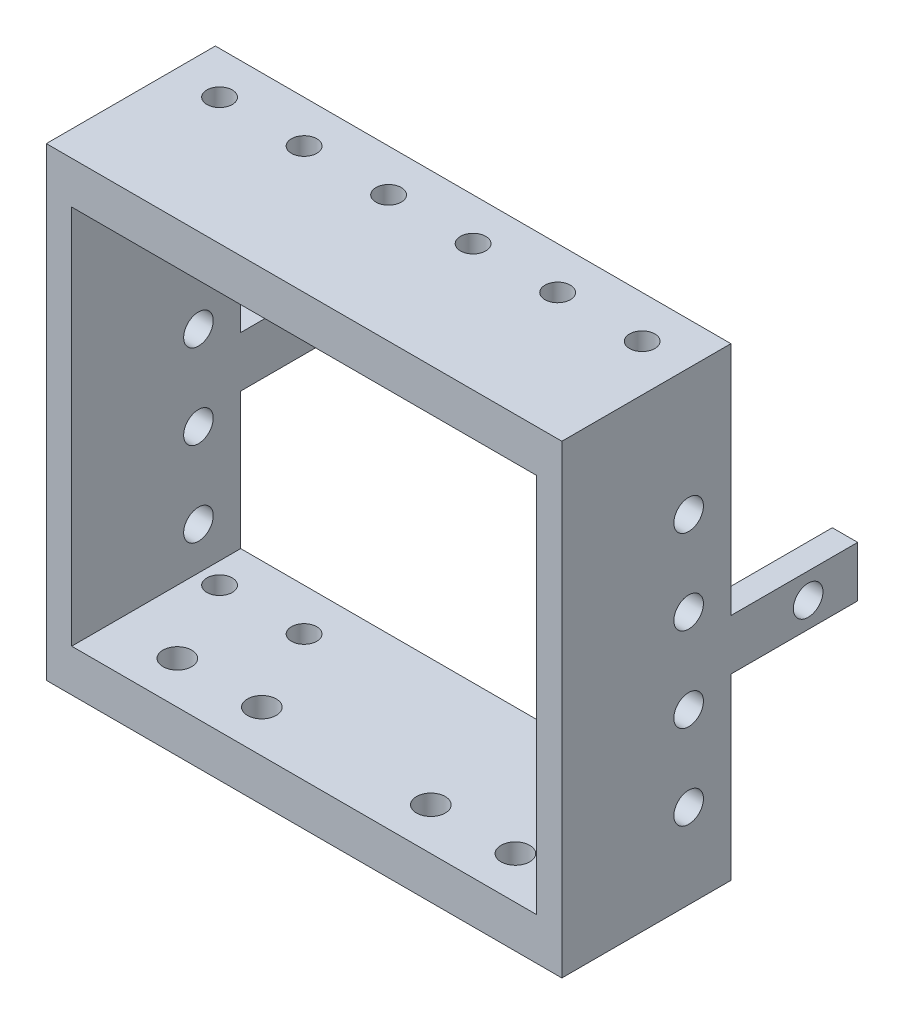
SolidWorks part; units mm, degrees
ref_plane "Front Plane" through (0, 0, 0) normal (0, 0, 1) x (1, 0, 0)
ref_plane "Top Plane" through (0, 0, 0) normal (0, 1, 0) x (1, 0, 0)
ref_plane "Right Plane" through (0, 0, 0) normal (1, 0, 0) x (0, 0, -1)
sketch "Sketch1" plane through (0, 0, 0) normal (0, 1, 0) x (1, 0, 0)
  line L1 (-23.3554, -4.3957) -> (37.6446, -4.3957)
  line L2 (-23.3554, -4.3957) -> (-23.3554, 5.6043)
  line L3 (-23.3554, 5.6043) -> (37.6446, 5.6043)
  line L4 (37.6446, -4.3957) -> (37.6446, 5.6043)
  circle A0 centre (-17.8554, 0.6043) radius 1.5
  circle A1 centre (-7.8554, 0.6043) radius 1.5
  circle A2 centre (22.1446, 0.6043) radius 1.5
  circle A3 centre (32.1446, 0.6043) radius 1.5
  dimension "D5" = 3
  dimension "D1" = 10
  dimension "D2" = 10
  dimension "D3" = 5.5
  dimension "D4" = 5.5
  dimension "D6" = 10
  dimension "D7" = 30
  dimension "D8" = 5
extrude "Boss-Extrude1" add sketch "Sketch1" along normal blind 5
sketch "Sketch2" plane through (0, 5, 0) normal (0, 1, 0) x (1, 0, 0)
  line L0 (37.6446, -4.3957) -> (37.6446, 5.6043) construction
  line L1 (-23.3554, -4.3957) -> (37.6446, -4.3957) construction
  line L2 (-23.3554, 5.6043) -> (-23.3554, -4.3957) construction
  line L3 (37.6446, 5.6043) -> (-23.3554, 5.6043) construction
  line L4 (37.6446, -4.3957) -> (37.6446, 5.6043)
  line L5 (-23.3554, -4.3957) -> (-20.3554, -4.3957)
  line L6 (-23.3554, 5.6043) -> (-23.3554, -4.3957)
  line L7 (37.6446, 5.6043) -> (34.6446, 5.6043)
  line L8 (-20.3554, 5.6043) -> (-20.3554, -4.3957)
  line L9 (34.6446, 5.6043) -> (34.6446, -4.3957)
  line L10 (-20.3554, 5.6043) -> (-23.3554, 5.6043)
  line L11 (34.6446, -4.3957) -> (37.6446, -4.3957)
  dimension "D1" = 3
  dimension "D2" = 3
extrude "Boss-Extrude2" add sketch "Sketch2" along normal blind 45
sketch "Sketch3" plane through (-23.3554, 0, 0) normal (-1, 0, 0) x (0, 0, 1)
  line L0 (-5.6043, 5) -> (4.3957, 5) construction
  line L1 (-5.6043, 5) -> (4.3957, 5) construction
  line L2 (-5.6043, 50) -> (-5.6043, 0) construction
  circle A0 centre (-0.6043, 10) radius 1.75
  dimension "D1" = 3.5
  dimension "D2" = 5
  dimension "D3" = 5
extrude "Cut-Extrude1" cut sketch "Sketch3" against normal through all contours A0
sketch "Sketch4" plane through (-23.3554, 0, 0) normal (-1, 0, 0) x (0, 0, 1)
  line L0 (-5.6043, 50) -> (-5.6043, 0) construction
  line L1 (-5.6043, 21.14) -> (-20.6043, 21.14)
  line L2 (-5.6043, 21.14) -> (-5.6043, 27.14)
  line L3 (-5.6043, 27.14) -> (-20.6043, 27.14)
  line L4 (-20.6043, 21.14) -> (-20.6043, 27.14)
  circle A0 centre (-14.7443, 24.14) radius 1.75
  circle A1 centre (-0.6043, 10) radius 1.75 construction
  dimension "D1" = 3.5
  dimension "D3" = 14.14
  dimension "D5" = 3
  dimension "D2" = 14.14
  dimension "D4" = 6
  dimension "D6" = 15
extrude "Boss-Extrude3" add sketch "Sketch4" against normal blind 3 contours L1 L4 L3 L2
ref_plane "Plane1" through (7.1446, 0, 0) normal (-1, 0, 0) x (0, 0, 1)
mirror "Mirror1" about plane through (7.1446, 0, 0) normal (-1, 0, 0) of "Boss-Extrude3"
sketch "Sketch5" plane through (-23.3554, 0, 0) normal (-1, 0, 0) x (0, 0, 1)
  circle A0 centre (-14.7443, 24.14) radius 1.75
  circle A1 centre (-0.6043, 10) radius 1.75 construction
  dimension "D1" = 3.5
  dimension "D2" = 14.14
  dimension "D3" = 14.14
extrude "Cut-Extrude2" cut sketch "Sketch5" against normal through all
sketch "Sketch6" plane through (0, 50, 0) normal (0, 1, 0) x (1, 0, 0)
  line L0 (7.1446, 13.75) -> (7.1446, -13.75) construction
  line L1 (-23.3554, -4.3957) -> (37.6446, -4.3957)
  line L2 (-23.3554, -4.3957) -> (-23.3554, 5.6043)
  line L3 (-23.3554, 5.6043) -> (37.6446, 5.6043)
  line L4 (37.6446, -4.3957) -> (37.6446, 5.6043)
  circle A0 centre (2.1446, 0.6043) radius 1.5
  circle A1 centre (12.1446, 0.6043) radius 1.5
  circle A2 centre (-7.8554, 0.6043) radius 1.5
  circle A3 centre (-17.8554, 0.6043) radius 1.5
  circle A4 centre (22.1446, 0.6043) radius 1.5
  circle A5 centre (32.1446, 0.6043) radius 1.5
  dimension "D1" = 3
  dimension "D2" = 5
  dimension "D3" = 5
  dimension "D4" = 3
  dimension "D5" = 3
extrude "Boss-Extrude4" add sketch "Sketch6" along normal blind 5
sketch "Sketch7" plane through (-23.3554, 0, 0) normal (-1, 0, 0) x (0, 0, 1)
  circle A0 centre (-0.6043, 10) radius 1.75 construction
  circle A1 centre (-0.6043, 10) radius 1.75
  circle A2 centre (-0.6043, 20) radius 1.75
  circle A3 centre (-0.6043, 30) radius 1.75
  circle A4 centre (-0.6043, 40) radius 1.75
  circle A6 centre (-0.6043, 50) radius 1.75 [skipped]
  dimension "D1" = 5
extrude "Cut-Extrude3" cut sketch "Sketch7" against normal through all
sketch "Sketch8" plane through (0, 0, 4.3957) normal (0, 0, 1) x (1, 0, 0)
  line L0 (37.6446, 55) -> (37.6446, 0) construction
  line L1 (-20.3554, 50) -> (34.6446, 50)
  line L2 (-20.3554, 50) -> (-20.3554, 5)
  line L3 (-20.3554, 5) -> (34.6446, 5)
  line L4 (34.6446, 50) -> (34.6446, 5)
  line L5 (-23.3554, 55) -> (37.6446, 55)
  line L6 (-23.3554, 55) -> (-23.3554, 0)
  line L7 (-23.3554, 0) -> (37.6446, 0)
  line L8 (37.6446, 55) -> (37.6446, 0)
extrude "Boss-Extrude5" add sketch "Sketch8" along normal blind 10
sketch "Sketch13" plane through (0, 0, 0) normal (0, -1, 0) x (1, 0, 0)
  line L0 (7.1446, 13.75) -> (7.1446, -13.75) construction
  line L1 (-23.3554, 14.3957) -> (37.6446, 14.3957) construction
  circle A0 centre (-2.8554, 9.3957) radius 1.7
  circle A1 centre (-12.8554, 9.3957) radius 1.7
  circle A2 centre (17.1446, 9.3957) radius 1.7
  circle A3 centre (27.1446, 9.3957) radius 1.7
  dimension "D1" = 3.4
  dimension "D2" = 10
  dimension "D3" = 10
  dimension "D4" = 5
extrude "Cut-Extrude5" cut sketch "Sketch13" against normal blind 18
